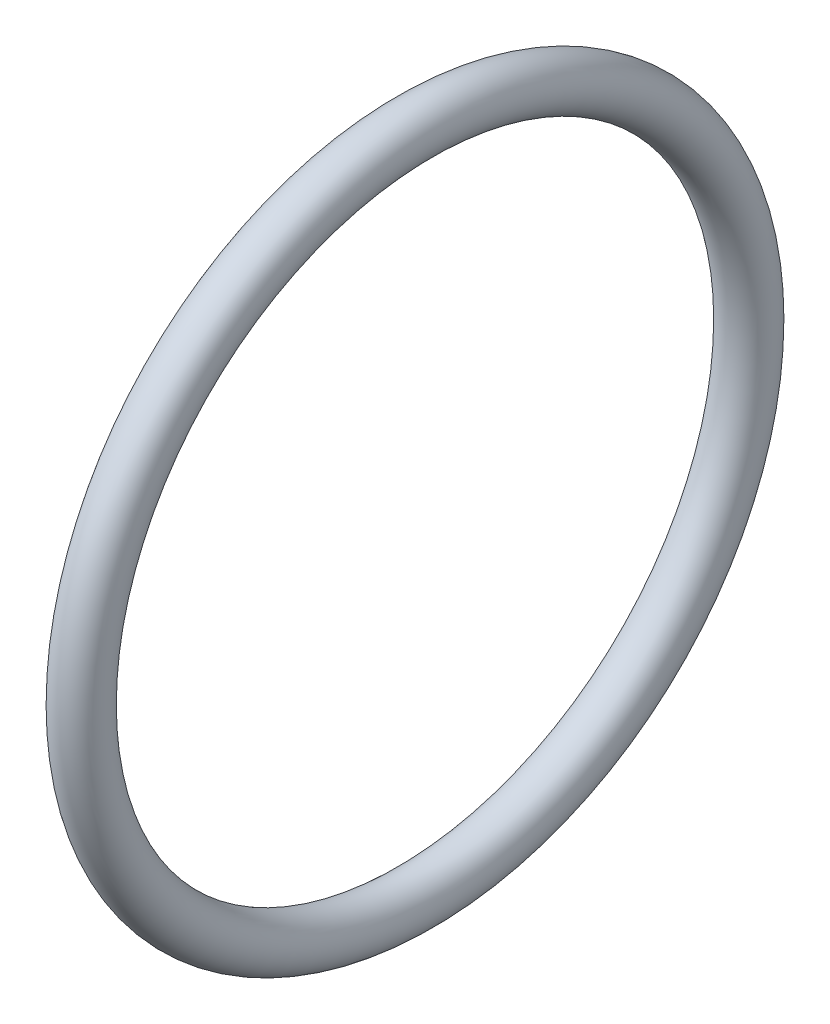
SolidWorks part; units mm, degrees
ref_plane "前视基准面" through (0, 0, 0) normal (0, 0, 1) x (1, 0, 0)
ref_plane "上视基准面" through (0, 0, 0) normal (0, 1, 0) x (1, 0, 0)
ref_plane "右视基准面" through (0, 0, 0) normal (1, 0, 0) x (0, 0, -1)
sketch "草图1" plane through (0, 0, 0) normal (0, 0, 1) x (1, 0, 0)
  line L0 (0, 0) -> (24.9916, 0) construction
  circle A0 centre (0, 21.5) radius 1.6
  dimension "D1" = 3.2
  dimension "D2" = 21.5
revolve "旋转1" add sketch "草图1" angle 360 about L0
